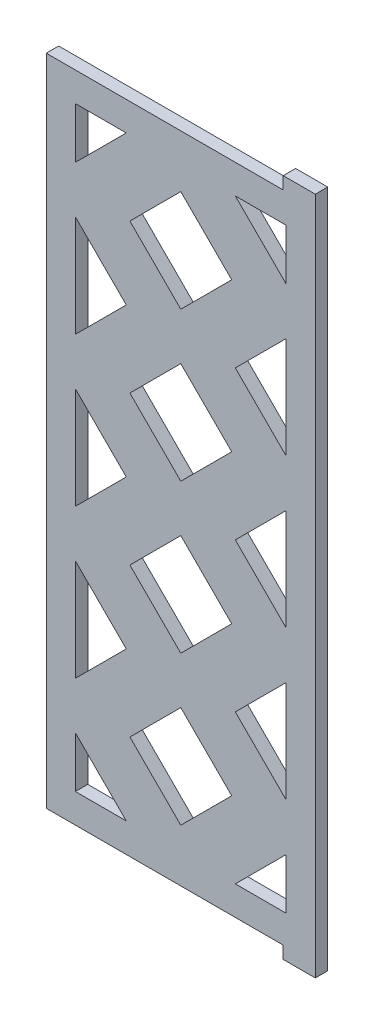
SolidWorks part; units mm, degrees
ref_plane "Alzado" through (0, 0, 0) normal (0, 0, 1) x (1, 0, 0)
ref_plane "Planta" through (0, 0, 0) normal (0, 1, 0) x (1, 0, 0)
ref_plane "Vista lateral" through (0, 0, 0) normal (1, 0, 0) x (0, 0, -1)
sketch "Croquis1" plane through (0, 0, 0) normal (0, 0, 1) x (1, 0, 0)
  line L1 (-32.5, 0) -> (24.75, 0)
  line L3 (-32.5, 0) -> (-32.5, -158)
  line L4 (32.5, 0) -> (32.5, -158)
  line L6 (-32.5, -158) -> (24.75, -158)
  line L7 (32.5, 0) -> (32.5, 3)
  line L21 (32.5, 3) -> (24.75, 3)
  line L22 (24.75, 3) -> (24.75, 0)
  line L24 (32.5, -79) -> (45.8241, -79) construction
  line L28 (32.5, -158) -> (32.5, -161)
  line L38 (32.5, -161) -> (24.75, -161)
  line L40 (24.75, -161) -> (24.75, -158)
  line L48 (-13.175, -7.03) -> (-25.475, -19.33)
  line L49 (-13.175, -7.03) -> (-25.475, -7.03)
  line L50 (-25.475, -7.03) -> (-25.475, -19.33)
  line L51 (13.175, -7.03) -> (25.475, -7.03)
  line L52 (13.175, -7.03) -> (25.475, -19.33)
  line L53 (25.475, -7.03) -> (25.475, -19.33)
  line L54 (13.175, -79) -> (25.475, -66.7)
  line L55 (13.175, -150.97) -> (25.475, -138.67)
  line L56 (25.475, -91.3) -> (25.475, -66.7)
  line L59 (-13.175, -79) -> (-25.475, -66.7)
  line L60 (-25.475, -91.3) -> (-25.475, -66.7)
  line L61 (13.175, -43.015) -> (25.475, -55.315)
  line L62 (25.475, -150.97) -> (25.475, -138.67)
  line L63 (13.175, -43.015) -> (25.475, -30.715)
  line L64 (25.475, -55.315) -> (25.475, -30.715)
  line L67 (-13.175, -43.015) -> (-25.475, -30.715)
  line L68 (-25.475, -55.315) -> (-25.475, -30.715)
  line L69 (-13.175, -43.015) -> (-25.475, -55.315)
  line L73 (0, -48.7075) -> (-12.3, -61.0075)
  line L74 (-12.3, -61.0075) -> (0, -73.3075)
  line L75 (0, -73.3075) -> (12.3, -61.0075)
  line L76 (12.3, -61.0075) -> (0, -48.7075)
  line L78 (13.175, -150.97) -> (25.475, -150.97)
  line L79 (0, -12.7225) -> (12.3, -25.0225)
  line L80 (-12.3, -25.0225) -> (0, -12.7225)
  line L81 (0, -37.3225) -> (-12.3, -25.0225)
  line L82 (12.3, -25.0225) -> (0, -37.3225)
  line L83 (-13.175, -150.97) -> (-25.475, -150.97)
  line L84 (-13.175, -150.97) -> (-25.475, -138.67)
  line L85 (-25.475, -150.97) -> (-25.475, -138.67)
  line L86 (-13.175, -114.985) -> (-25.475, -127.285)
  line L87 (-25.475, -102.685) -> (-25.475, -127.285)
  line L88 (-13.175, -114.985) -> (-25.475, -102.685)
  line L89 (-12.3, -132.9775) -> (0, -145.2775)
  line L90 (0, -120.6775) -> (-12.3, -132.9775)
  line L91 (12.3, -132.9775) -> (0, -120.6775)
  line L92 (0, -145.2775) -> (12.3, -132.9775)
  line L93 (13.175, -114.985) -> (25.475, -127.285)
  line L94 (25.475, -102.685) -> (25.475, -127.285)
  line L95 (13.175, -114.985) -> (25.475, -102.685)
  line L96 (13.175, -79) -> (25.475, -91.3)
  line L97 (0, -84.6925) -> (12.3, -96.9925)
  line L98 (-12.3, -96.9925) -> (0, -84.6925)
  line L99 (0, -109.2925) -> (-12.3, -96.9925)
  line L100 (12.3, -96.9925) -> (0, -109.2925)
  line L101 (-13.175, -79) -> (-25.475, -91.3)
  point P41 (-25.475, -7.03)
  dimension "D1" = 3
  dimension "D2" = 7.75
  dimension "D3" = 32.5
  dimension "D9" = 12.3
extrude "Saliente-Extruir1" add sketch "Croquis1" along normal blind 3
